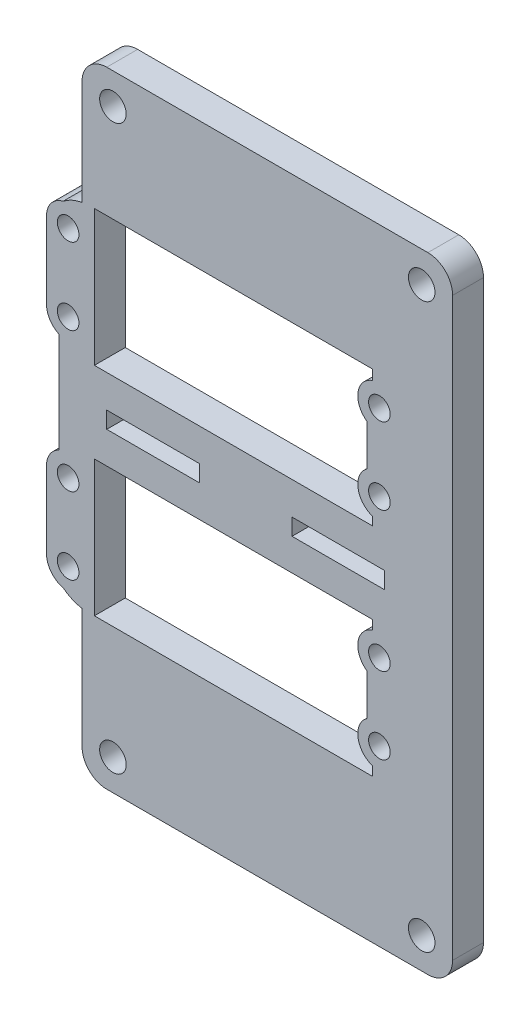
SolidWorks part; units mm, degrees
ref_plane "Front Plane" through (0, 0, 0) normal (0, 0, 1) x (1, 0, 0)
ref_plane "Top Plane" through (0, 0, 0) normal (0, 1, 0) x (1, 0, 0)
ref_plane "Right Plane" through (0, 0, 0) normal (1, 0, 0) x (0, 0, -1)
sketch "Sketch1" plane through (0, 0, 0) normal (0, 0, 1) x (1, 0, 0)
  line L0 (32.0508, 59.7804) -> (32.0508, -27.1654) construction
  line L1 (37.0508, 16.3075) -> (33.0508, 16.3075) construction
  line L2 (29.9008, -29.3154) -> (21.2052, -29.3154) construction
  line L3 (-20.9492, 46.1222) -> (24.0508, 46.1222)
  line L4 (33.0508, 66.9304) -> (-18.9492, 66.9304)
  line L5 (37.0508, 62.9304) -> (37.0508, -30.3154)
  line L6 (33.0508, -34.3154) -> (-18.9492, -34.3154)
  line L7 (-22.9492, 62.9304) -> (-22.9492, 45.9592)
  line L8 (-20.9492, 46.1222) -> (-20.9492, 24.1222)
  line L9 (-20.9492, 24.1222) -> (24.0508, 24.1222)
  line L10 (24.0508, 46.1222) -> (24.0508, 44.506)
  line L12 (-20.9492, 11.0016) -> (24.0508, 11.0016)
  line L13 (-20.9492, 11.0016) -> (-20.9492, -10.9984)
  line L14 (-20.9492, -10.9984) -> (24.0508, -10.9984)
  line L15 (24.0508, 11.0016) -> (24.0508, 9.506)
  line L16 (24.0508, -9.506) -> (24.0508, -10.9984)
  line L17 (0, 11.0016) -> (0, 12.4032) construction
  line L18 (-28.7, -6.2) -> (-28.7, 6.2)
  line L19 (43.5652, 17.5) -> (41.4948, 17.5) construction
  line L20 (-26.6785, 9.3724) -> (-26.6785, 25.6276)
  line L21 (-22.9492, -30.3154) -> (-22.9492, -10.9592)
  line L22 (-28.7, 41.2) -> (-28.7, 28.8)
  line L23 (-3.9492, 18.85) -> (-18.9492, 18.85)
  line L24 (-18.9492, 18.85) -> (-18.9492, 16.15)
  line L25 (-18.9492, 16.15) -> (-3.9492, 16.15)
  line L26 (-3.9492, 16.15) -> (-3.9492, 18.85)
  line L27 (26.0508, 18.85) -> (11.0508, 18.85)
  line L28 (11.0508, 18.85) -> (11.0508, 16.15)
  line L29 (11.0508, 16.15) -> (26.0508, 16.15)
  line L30 (26.0508, 16.15) -> (26.0508, 18.85)
  line L31 (23.2081, 3.3221) -> (23.2081, -3.3221)
  line L32 (24.0508, 23.9984) -> (24.0508, 25.494)
  line L33 (24.0508, 25.494) -> (24.0508, 24.1222)
  line L34 (23.2081, 31.6779) -> (23.2081, 38.3221)
  circle A0 centre (-25.2, -6.2) radius 1.75
  circle A1 centre (-25.2, 6.2) radius 1.75
  arc A4 (-18.9492, 66.9304) -> (-22.9492, 62.9304) centre (-18.9492, 62.9304) ccw
  arc A5 (-18.9492, -34.3154) -> (-22.9492, -30.3154) centre (-18.9492, -30.3154) cw
  arc A6 (37.0508, -30.3154) -> (33.0508, -34.3154) centre (33.0508, -30.3154) cw
  arc A7 (33.0508, 66.9304) -> (37.0508, 62.9304) centre (33.0508, 62.9304) cw
  circle A8 centre (-17.9492, 61.9304) radius 2.15
  circle A9 centre (32.0508, 61.9304) radius 2.15
  circle A10 centre (32.0508, -29.3154) radius 2.15
  circle A11 centre (-17.9492, -29.3154) radius 2.15
  arc A13 (-28.7, -6.2) -> (-26.0152, -9.6037) centre (-25.2, -6.2) ccw
  arc A15 (-26.6785, 9.3724) -> (-28.7, 6.2) centre (-25.2, 6.2) ccw
  arc A16 (-28.7, 41.2) -> (-26.0152, 44.6037) centre (-25.2, 41.2) cw
  arc A17 (-26.6785, 25.6276) -> (-28.7, 28.8) centre (-25.2, 28.8) cw
  arc A18 (23.2081, 38.3221) -> (24.0508, 44.506) centre (25.2, 41.2) cw
  arc A19 (24.0508, 25.494) -> (23.2081, 31.6779) centre (25.2, 28.8) cw
  circle A21 centre (25.2, 28.8) radius 1.75
  arc A24 (24.0508, 9.506) -> (23.2081, 3.3221) centre (25.2, 6.2) ccw
  arc A25 (23.2081, -3.3221) -> (24.0508, -9.506) centre (25.2, -6.2) ccw
  circle A26 centre (25.2, 41.2) radius 1.75
  circle A27 centre (-25.2, 28.8) radius 1.75
  circle A28 centre (-25.2, 41.2) radius 1.75
  circle A30 centre (25.2, 6.2) radius 1.75
  circle A31 centre (25.2, -6.2) radius 1.75
  spline S0 degree 3 poles (-26.0152, -9.6037) (-25.073, -10.3271) (-24.051, -10.779) (-22.9492, -10.9592) knots 0 0 0 0 0.632661 0.632661 0.632661 0.632661
  spline S1 degree 3 poles (-26.0152, 44.6037) (-25.073, 45.3271) (-24.051, 45.779) (-22.9492, 45.9592) knots 0 0 0 0 0.632661 0.632661 0.632661 0.632661
  point P79 (-26.6785, 17.5)
  point P86 (0, 0)
  dimension "D2" = 101.2458
  dimension "D5" = 4
  dimension "D14" = 3.5
  dimension "D15" = 3.5
  dimension "D16" = 3.5
  dimension "D17" = 3.5
  dimension "D20" = 3.5
  dimension "D21" = 3.5
  dimension "D22" = 7
  dimension "D23" = 7
  dimension "D1" = 5
  dimension "D3" = 5
  dimension "D7" = 22
  dimension "D8" = 2
  dimension "D9" = 45
  dimension "D10" = 22
  dimension "D11" = 2
  dimension "D12" = 7.8146
  dimension "D13" = 5.306
extrude "Boss-Extrude1" add sketch "Sketch1" along normal blind 5
